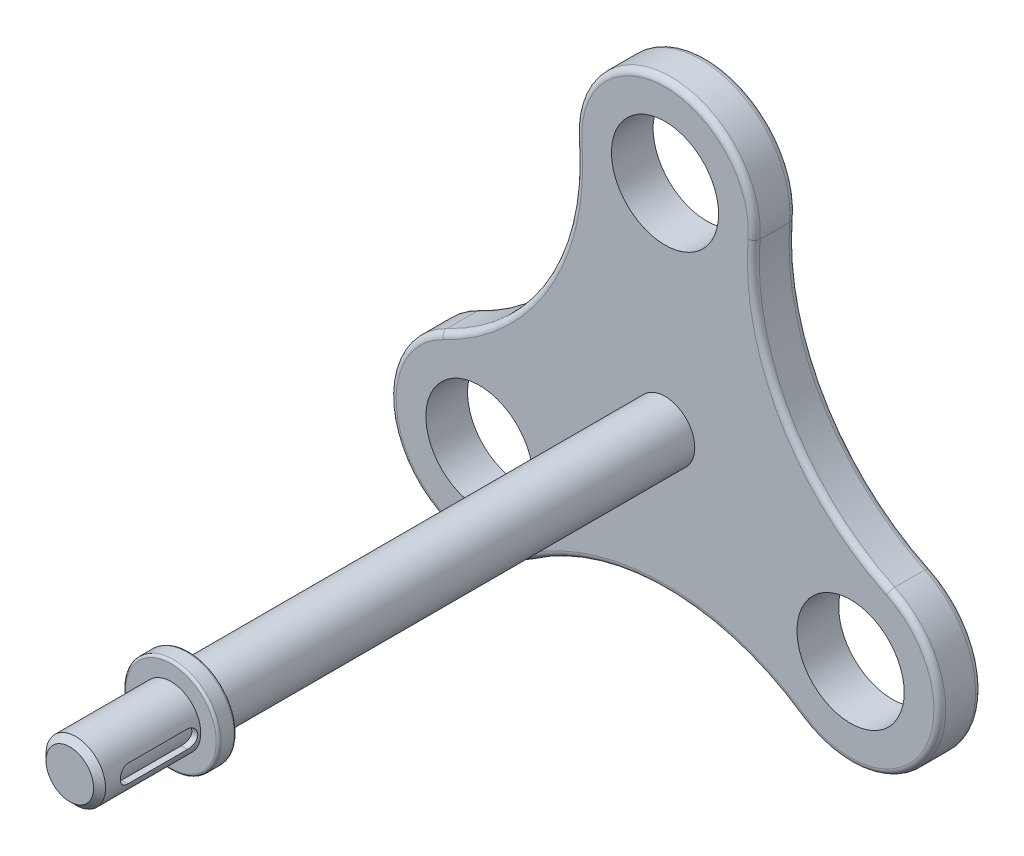
SolidWorks part; units mm, degrees
material "AISI 1020"
ref_plane "Front Plane" through (0, 0, 0) normal (0, 0, 1) x (1, 0, 0)
ref_plane "Top Plane" through (0, 0, 0) normal (0, 1, 0) x (1, 0, 0)
ref_plane "Right Plane" through (0, 0, 0) normal (1, 0, 0) x (0, 0, -1)
sketch "Sketch1" plane through (0, 0, 0) normal (0, 0, 1) x (1, 0, 0)
  circle A0 centre (0, 18) radius 7.5
  circle A1 centre (0, 18) radius 4.5
  circle A2 centre (15.5885, -9) radius 7.5
  circle A3 centre (15.5885, -9) radius 4.5
  circle A4 centre (-15.5885, -9) radius 7.5
  circle A5 centre (-15.5885, -9) radius 4.5
  arc A6 (18.8136, -2.2289) -> (7.4766, 17.4075) centre (27.4141, 15.8275) cw
  arc A7 (-11.3371, -15.1786) -> (11.3371, -15.1786) centre (0, -31.655) cw
  arc A8 (-7.4766, 17.4075) -> (-18.8136, -2.2289) centre (-27.4141, 15.8275) cw
  point P13 (0, 0)
  point P22 (0, 0)
  dimension "D1" = 15
  dimension "D2" = 9
  dimension "D5" = 20
  dimension "D6" = 3
  dimension "D3" = 18
  dimension "D4" = 3
extrude "Boss-Extrude1" add sketch "Sketch1" along normal blind 3.5 contours A0 A1 | A4 A5 | A2 A3 | A0 A8 A4 A7 A2 A6
sketch "Sketch2" plane through (0, 0, 3.5) normal (0, 0, 1) x (1, 0, 0)
  circle A0 centre (0, 0) radius 2.5
  dimension "D1" = 5
extrude "Boss-Extrude2" add sketch "Sketch2" along normal blind 50
sketch "Sketch3" plane through (0, 0, 53.5) normal (0, 0, 1) x (1, 0, 0)
  circle A0 centre (0, 0) radius 4
  dimension "D1" = 8
extrude "Boss-Extrude3" add sketch "Sketch3" along normal blind 1.5 from offset 10 offset against normal yes
sketch "Sketch4" plane through (0, 0, 0) normal (1, 0, 0) x (0, 0, -1)
  line L0 (-51, 0) -> (-46, 0) construction
  line L1 (-51, 0.75) -> (-46, 0.75)
  line L2 (-51, -0.75) -> (-46, -0.75)
  line L3 (-53.5, 2.5) -> (-53.5, -2.5) construction
  arc A0 (-51, 0.75) -> (-51, -0.75) centre (-51, 0) ccw
  arc A1 (-46, -0.75) -> (-46, 0.75) centre (-46, 0) ccw
  point P2 (-48.5, 0)
  dimension "D1" = 5
  dimension "D2" = 5
  dimension "D3" = 1.5
extrude "Cut-Extrude1" cut sketch "Sketch4" against normal offset from surface (3.146 mm away) 0.5 from offset 5
chamfer "Chamfer1" distance 0.5 angle 45 1 edges at (2.5, 0, 53.5)
fillet "Fillet1" radius 0.2 2 edges at (4, 0, 43.5) (4, 0, 45)
fillet "Fillet3" radius 0.5 12 edges at (22.0836, -12.75, 0) (22.0836, -12.75, 3.5) (0, -11.655, 0) (0, -11.655, 3.5) (-22.0836, -12.75, 0) (-22.0836, -12.75, 3.5) (-10.0935, 5.8275, 0) (-10.0935, 5.8275, 3.5) (0, 25.5, 0) (0, 25.5, 3.5) (10.0935, 5.8275, 0) (10.0935, 5.8275, 3.5)
